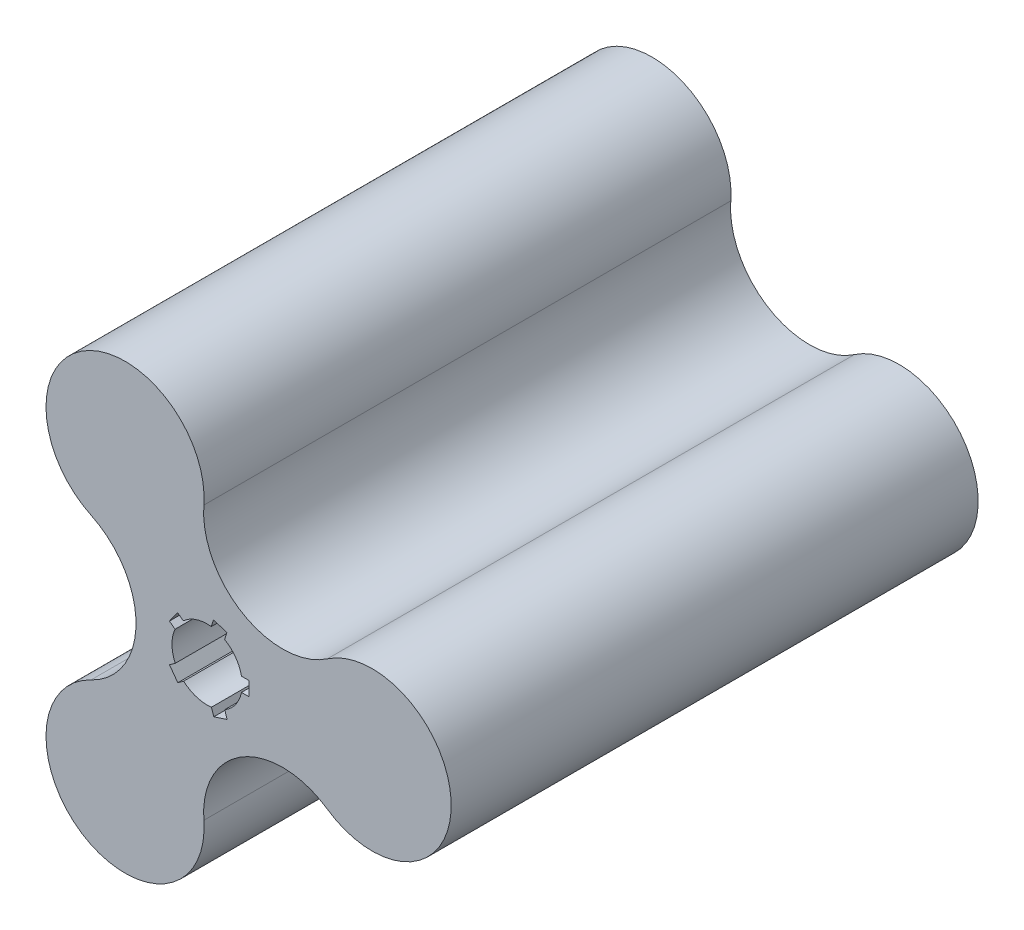
SolidWorks part; units mm, degrees
ref_plane "Front Plane" through (0, 0, 0) normal (0, 0, 1) x (1, 0, 0)
ref_plane "Top Plane" through (0, 0, 0) normal (0, 1, 0) x (1, 0, 0)
ref_plane "Right Plane" through (0, 0, 0) normal (1, 0, 0) x (0, 0, -1)
sketch "Sketch1" plane through (0, 0, 0) normal (0, 0, 1) x (1, 0, 0)
  line L0 (0.671, -8.1531) -> (4.4753, -6.917)
  line L1 (8, -2) -> (12, -2)
  line L2 (8, -2) -> (8, 2)
  line L3 (8, 2) -> (12, 2)
  line L4 (12, -2) -> (12, 2)
  line L5 (8, -2) -> (12, 2) construction
  line L6 (8, 2) -> (12, -2) construction
  line L7 (0.671, -8.1531) -> (1.9071, -11.9573)
  line L8 (1.9071, -11.9573) -> (5.7113, -10.7212)
  line L9 (4.4753, -6.917) -> (5.7113, -10.7212)
  line L10 (-7.4457, -3.0842) -> (-5.0945, -6.3203)
  line L11 (-7.4457, -3.0842) -> (-10.6817, -5.4354)
  line L12 (-10.6817, -5.4354) -> (-8.3306, -8.6715)
  line L13 (-5.0945, -6.3203) -> (-8.3306, -8.6715)
  line L14 (-5.1331, 6.2016) -> (-7.4843, 2.9655)
  line L15 (-5.1331, 6.2016) -> (-8.3692, 8.5527)
  line L16 (-8.3692, 8.5527) -> (-10.7203, 5.3166)
  line L17 (-7.4843, 2.9655) -> (-10.7203, 5.3166)
  line L18 (4.4128, 6.8717) -> (0.6086, 8.1077)
  line L19 (4.4128, 6.8717) -> (5.6489, 10.6759)
  line L20 (5.6489, 10.6759) -> (1.8447, 11.912)
  line L21 (0.6086, 8.1077) -> (1.8447, 11.912)
  circle A0 centre (0, 0) radius 10
  arc A1 (34.2565, -18.5761) -> (34.2565, 18.5104) centre (47, -0.0328) ccw
  arc A2 (-33.0356, -20.3407) -> (-0.9178, -38.8839) centre (-23.3485, -40.6485) ccw
  arc A3 (-0.9178, 38.8183) -> (-33.0356, 20.275) centre (-23.3485, 40.5829) ccw
  arc A4 (-0.9178, 38.8183) -> (34.2565, 18.5104) centre (21.5129, 37.0537) ccw
  circle A5 centre (0.101, -0.0328) radius 46.899 construction
  arc A6 (34.2565, -18.5761) -> (-0.9178, -38.8839) centre (21.5129, -37.1193) ccw
  arc A7 (-33.0356, -20.3407) -> (-33.0356, 20.275) centre (-42.7228, -0.0328) ccw
  point P3 (10, 0)
  point P9 (-6.7511, 7.3771)
  point P10 (-9.1023, 4.1411)
  point P26 (0.101, -0.0328)
  point P35 (0.101, -0.0328)
  point P47 (0.101, -0.0328)
  dimension "D1" = 20
  dimension "D5" = 45
  dimension "D8" = 22.5
  dimension "D2" = 4
  dimension "D3" = 4
  dimension "D6" = 47
  dimension "D4" = 5
  dimension "D7" = 3
  dimension "D9" = 3
extrude "Boss-Extrude1" add sketch "Sketch1" along normal mid plane 150 contours A7 A2 A6 A1 A4 A3 A0 L3 L4 L1 L9 L8 L7 L13 L12 L11 L17 L16 L15 L21 L20 L19
